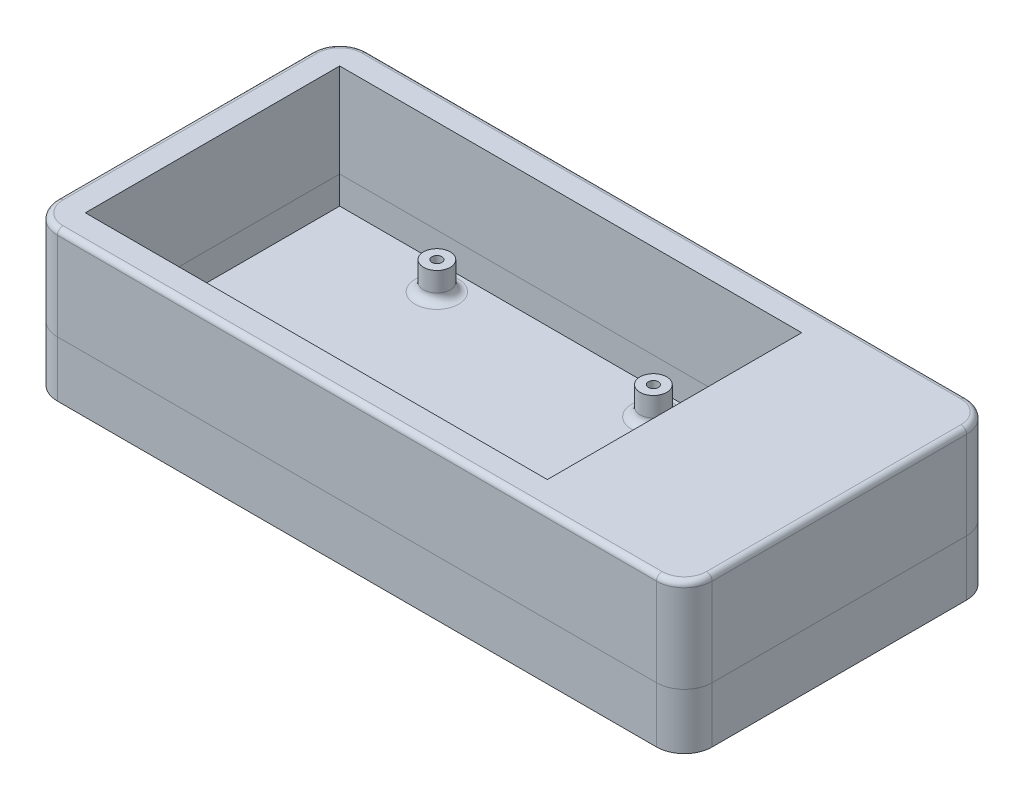
SolidWorks part; units mm, degrees
ref_plane "Front Plane" through (0, 0, 0) normal (0, 0, 1) x (1, 0, 0)
ref_plane "Top Plane" through (0, 0, 0) normal (0, 1, 0) x (1, 0, 0)
ref_plane "Right Plane" through (0, 0, 0) normal (1, 0, 0) x (0, 0, -1)
sketch "Sketch1" plane through (0, 0, 0) normal (0, 1, 0) x (1, 0, 0)
  line L1 (-44.3337, 20.1048) -> (63.2663, 20.1048)
  line L2 (-44.3337, 20.1048) -> (-44.3337, -25.5852)
  line L3 (-44.3337, -25.5852) -> (63.2663, -25.5852)
  line L4 (63.2663, 20.1048) -> (63.2663, -25.5852)
  line L5 (-44.3337, 20.1048) -> (63.2663, 20.1048)
  line L7 (-44.3337, 25.1048) -> (63.2663, 25.1048)
  line L10 (-44.3337, 20.1048) -> (-44.3337, -25.5852)
  line L12 (-49.3337, 20.1048) -> (-49.3337, -25.5852)
  line L14 (63.2663, 20.1048) -> (63.2663, -25.5852)
  line L16 (68.2663, 20.1048) -> (68.2663, -25.5852)
  line L17 (-44.3337, -25.5852) -> (63.2663, -25.5852)
  line L19 (-44.3337, -30.5852) -> (63.2663, -30.5852)
  arc A0 (-49.3337, 20.1048) -> (-44.3337, 25.1048) centre (-44.3337, 20.1048) cw
  arc A2 (68.2663, -25.5852) -> (63.2663, -30.5852) centre (63.2663, -25.5852) cw
  arc A3 (-44.3337, -30.5852) -> (-49.3337, -25.5852) centre (-44.3337, -25.5852) cw
  arc A4 (63.2663, 25.1048) -> (68.2663, 20.1048) centre (63.2663, 20.1048) cw
  dimension "D1" = 107.6
  dimension "D2" = 45.69
  dimension "D3" = 5
  dimension "D4" = 5
  dimension "D5" = 5
  dimension "D6" = 5
  dimension "D7" = 45.69
  dimension "D8" = 107.6
  dimension "D9" = 107.6
extrude "Boss-Extrude2" add sketch "Sketch1" along normal blind 26.8 contours L12 A3 L19 A2 L16 A4 L7 A0
sketch "Sketch2" plane through (0, 26.8, 0) normal (0, 1, 0) x (1, 0, 0)
  line L1 (-44.3337, 20.1048) -> (63.2663, 20.1048)
  line L2 (-44.3337, 20.1048) -> (-44.3337, -25.5852)
  line L3 (-44.3337, -25.5852) -> (63.2663, -25.5852)
  line L4 (63.2663, 20.1048) -> (63.2663, -25.5852)
extrude "Cut-Extrude2" cut sketch "Sketch2" against normal blind 21.8
sketch "Sketch3" plane through (0, 5, 0) normal (0, 1, 0) x (1, 0, 0)
  line L0 (-44.3337, 20.1048) -> (-44.3337, -25.5852) construction
  line L1 (63.2663, 20.1048) -> (-44.3337, 20.1048) construction
  line L2 (63.2663, 20.1048) -> (-44.3337, 20.1048) construction
  circle A0 centre (-22.2837, 15.5148) radius 0.9
  circle A2 centre (16.6063, 15.5148) radius 0.9
  circle A3 centre (-2.4437, -20.9952) radius 0.9
  circle A4 centre (-22.2837, 15.5148) radius 2.4
  circle A5 centre (16.6063, 15.5148) radius 2.4
  circle A6 centre (-2.4437, -20.9952) radius 2.4
  dimension "D1" = 22.05
  dimension "D3" = 4.59
  dimension "D5" = 19.84
  dimension "D2" = 4.59
  dimension "D4" = 38.89
  dimension "D6" = 36.51
extrude "Boss-Extrude3" add sketch "Sketch3" along normal blind 5 contours A4 | A0 | A5 | A2 | A6 | A3
fillet "Fillet3" radius 1 8 edges at (-47.8693, 26.8, 29.1207) (-47.8693, 26.8, -23.6404) (66.8018, 26.8, -23.6404) (66.8018, 26.8, 29.1207) (9.4663, 26.8, -25.1048) (-49.3337, 26.8, 2.7402) (68.2663, 26.8, 2.7402) (9.4663, 26.8, 30.5852)
fillet "Fillet5" radius 1.5 1 edges at (16.6063, 5, -13.1148)
fillet "Fillet6" radius 1.5 1 edges at (-22.2837, 5, -13.1148)
fillet "Fillet7" radius 1.5 1 edges at (-2.4437, 5, 23.3952)
ref_plane "Plane1" through (0, 0, -20.1048) normal (0, 0, 1) x (1, 0, 0)
sketch "Sketch10" plane through (0, 0, -20.1048) normal (0, 0, 1) x (1, 0, 0)
  line L1 (63.2663, 26.8) -> (38.6563, 26.8)
  line L2 (63.2663, 26.8) -> (63.2663, 21.8)
  line L3 (63.2663, 21.8) -> (38.6563, 21.8)
  line L4 (38.6563, 26.8) -> (38.6563, 21.8)
  dimension "D1" = 24.61
  dimension "D2" = 5
extrude "Boss-Extrude4" add sketch "Sketch10" along normal up to next
sketch "Sketch13" plane through (0, 0, -20.1048) normal (0, 0, 1) x (1, 0, 0)
  line L0 (68.2663, 25.8) -> (68.2663, 0) construction
  line L1 (42.6263, 11) -> (52.6263, 11)
  line L2 (42.1263, 10.5) -> (42.1263, 7.2)
  line L3 (42.6263, 6.7) -> (52.6263, 6.7)
  line L4 (53.1263, 10.5) -> (53.1263, 7.2)
  line L6 (-44.3337, 0) -> (63.2663, 0) construction
  arc A0 (42.1263, 7.2) -> (42.6263, 6.7) centre (42.6263, 7.2) ccw
  arc A1 (52.6263, 6.7) -> (53.1263, 7.2) centre (52.6263, 7.2) ccw
  arc A2 (53.1263, 10.5) -> (52.6263, 11) centre (52.6263, 10.5) ccw
  arc A3 (42.1263, 10.5) -> (42.6263, 11) centre (42.6263, 10.5) cw
  point P10 (42.1263, 6.7)
  point P13 (53.1263, 6.7)
  point P16 (53.1263, 11)
  dimension "D5" = 0.5
  dimension "D1" = 11
  dimension "D2" = 4.3
  dimension "D3" = 15.14
  dimension "D4" = 11
extrude "Cut-Extrude3" cut sketch "Sketch13" against normal blind 5
sketch "Sketch14" plane through (0, 0, -20.1048) normal (0, 0, 1) x (1, 0, 0)
  line L0 (-49.3337, 10) -> (68.2663, 10)
  line L1 (-49.3337, 25.8) -> (-49.3337, 0) construction
  line L2 (68.2663, 25.8) -> (68.2663, 0) construction
  line L3 (63.2663, 0) -> (68.2663, 0) construction
  point P4 (67.3352, 5.6422)
  point P5 (68.2663, 5.6422)
  dimension "D1" = 10
split "Split1" trim tools "Sketch14" bodies to split 107 resulting bodies 108 109
